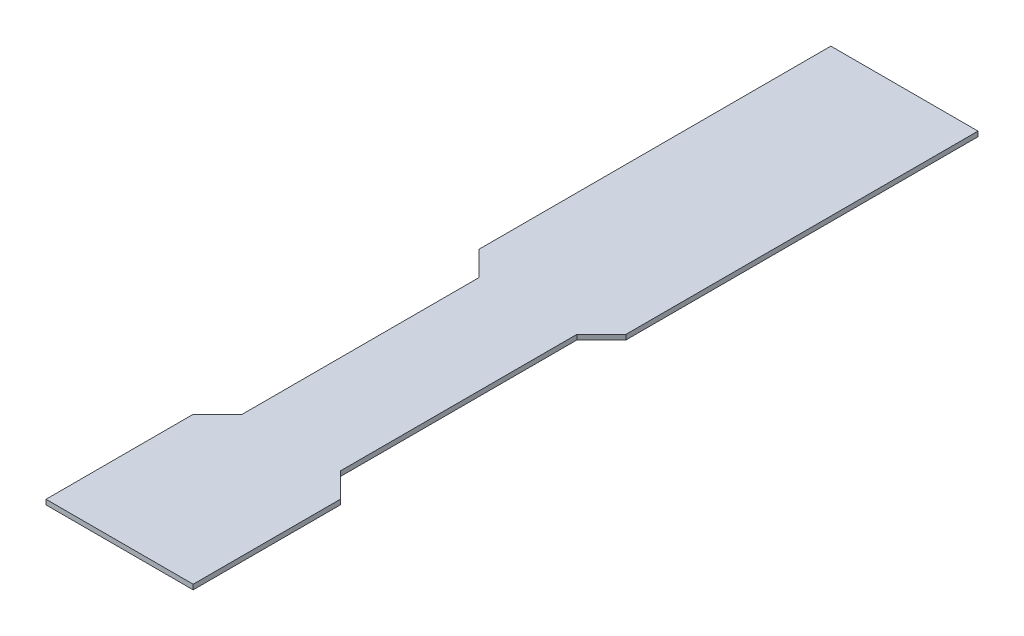
SolidWorks part; units mm, degrees
ref_plane "前视基准面" through (0, 0, 0) normal (0, 0, 1) x (1, 0, 0)
ref_plane "上视基准面" through (0, 0, 0) normal (0, 1, 0) x (1, 0, 0)
ref_plane "右视基准面" through (0, 0, 0) normal (1, 0, 0) x (0, 0, -1)
sketch "草图1" plane through (0, 0, 0) normal (0, 1, 0) x (1, 0, 0)
  line L0 (-30, -260) -> (-30, -320)
  line L6 (-30, -143.5) -> (-20, -153.5)
  line L8 (-20, -240) -> (-20, -153.5)
  line L21 (-30, -143.5) -> (-30, 0)
  line L22 (-30, -260) -> (-20, -250)
  line L23 (-20, -250) -> (-20, -240)
  line L24 (-30, -320) -> (30, -320)
  line L25 (-30, 0) -> (30, 0)
  line L27 (20, -250) -> (20, -240)
  line L28 (30, -260) -> (20, -250)
  line L29 (30, -143.5) -> (30, 0)
  line L30 (20, -240) -> (20, -153.5)
  line L31 (30, -143.5) -> (20, -153.5)
  line L32 (30, -260) -> (30, -320)
  point P12 (0, -320)
extrude "凸台-拉伸1" add sketch "草图1" along normal blind 2
